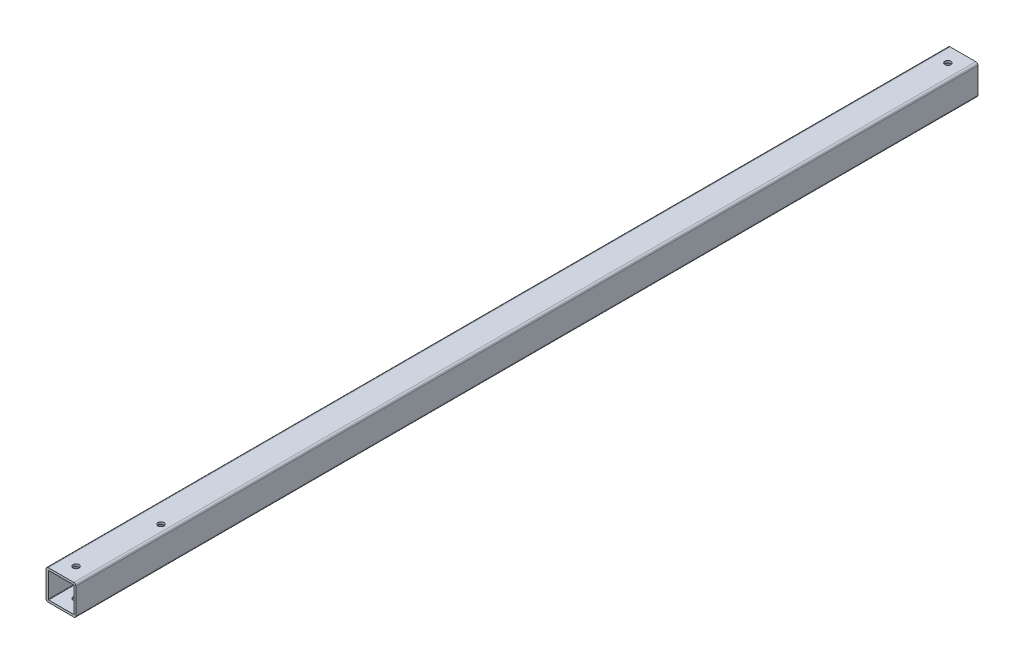
SolidWorks part; units mm, degrees
ref_plane "Front Plane" through (0, 0, 0) normal (0, 0, 1) x (1, 0, 0)
ref_plane "Top Plane" through (0, 0, 0) normal (0, 1, 0) x (1, 0, 0)
ref_plane "Right Plane" through (0, 0, 0) normal (1, 0, 0) x (0, 0, -1)
sketch "Sketch1" plane through (0, 0, 0) normal (0, 0, 1) x (1, 0, 0)
  line L1 (-20, 20) -> (20, 20)
  line L2 (-20, 20) -> (-20, -20)
  line L3 (-20, -20) -> (20, -20)
  line L4 (20, 20) -> (20, -20)
  line L5 (-20, 20) -> (20, -20) construction
  line L6 (-20, -20) -> (20, 20) construction
  point P0 (0, 0)
  dimension "D1" = 40
  dimension "D2" = 40
extrude "Extrude-Thin1" add sketch "Sketch1" along normal blind 1200 thin
fillet "Fillet1" radius 0.5 4 edges at (-17, -17, 600) (-17, 17, 600) (17, 17, 600) (17, -17, 600)
fillet "Fillet2" radius 3 4 edges at (20, -20, 600) (-20, -20, 600) (20, 20, 600) (-20, 20, 600)
hole_wizard "Ø8.0 (8) Diameter Hole1" positions "Sketch4" profile "Sketch3" hole size "Ø8.0" standard "ANSI Metric" end condition through all
sketch "Sketch4" plane through (0, 20, 0) normal (0, 1, 0) x (1, 0, 0)
  line L0 (0, 0) -> (0, -1200) construction
  line L1 (17, -1200) -> (-17, -1200) construction
  point P8 (0, -20)
  point P10 (0, -1180)
  dimension "D1" = 20
  dimension "D2" = 20
sketch "Sketch3" plane through (0, 20, 20) normal (1, 0, 0) x (0, 0, 1)
  line L0 (0, 0) -> (0, 40)
  line L1 (0, 40) -> (4, 40)
  line L2 (4, 40) -> (4, 0)
  line L5 (4, 0) -> (0, 0)
  line L11 (0, -6.35) -> (0, 107.95) construction
  dimension "Thru Hole Dia." = 8
  dimension "Thru Hole Depth" = 40
sketch "Sketch5" plane through (0, 20, 0) normal (0, 1, 0) x (1, 0, 0)
  line L0 (20, 0) -> (20, -1200) construction
  line L2 (17, -1200) -> (-17, -1200) construction
  circle A0 centre (8, -1075) radius 4
  dimension "D2" = 125
  dimension "D3" = 8
  dimension "D1" = 12
extrude "Cut-Extrude1" cut sketch "Sketch5" against normal through all
equation "\"a\"= \"Beam Profile@Plasma Beta.Assembly\""
equation "\"b\"= 3"
equation "\"L\"= \"Lenght@Plasma Beta.Assembly\""
equation "\"D2@Sketch1\"=\"a\""
equation "\"D1@Sketch1\"=\"a\""
equation "\"D1@Extrude-Thin1\"=\"L\""
equation "\"D5@Extrude-Thin1\"=\"b\""
equation "\"D1@Fillet2\"=\"b\""
